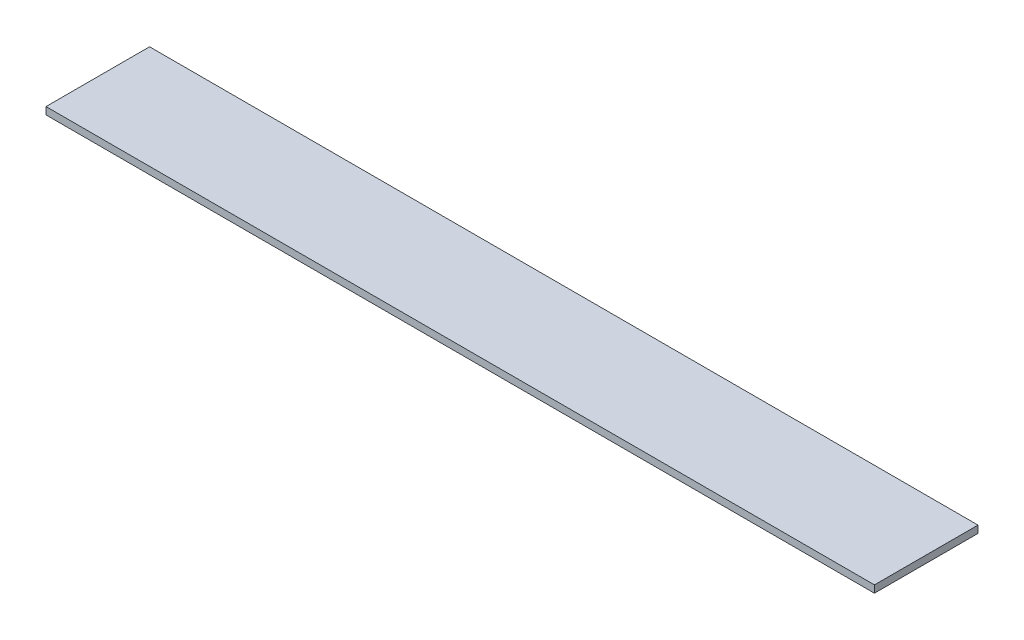
SolidWorks part; units mm, degrees
ref_plane "Front Plane" through (0, 0, 0) normal (0, 0, 1) x (1, 0, 0)
ref_plane "Top Plane" through (0, 0, 0) normal (0, 1, 0) x (1, 0, 0)
ref_plane "Right Plane" through (0, 0, 0) normal (1, 0, 0) x (0, 0, -1)
sketch "Sketch1" plane through (0, 0, 0) normal (0, 1, 0) x (1, 0, 0)
  line L1 (-40, -5) -> (40, -5)
  line L2 (-40, -5) -> (-40, 5)
  line L3 (-40, 5) -> (40, 5)
  line L4 (40, -5) -> (40, 5)
  line L5 (-40, -5) -> (40, 5) construction
  line L6 (-40, 5) -> (40, -5) construction
  point P0 (0, 0)
  dimension "D1" = 10
  dimension "D2" = 80
extrude "Boss-Extrude1" add sketch "Sketch1" along normal blind 0.7
